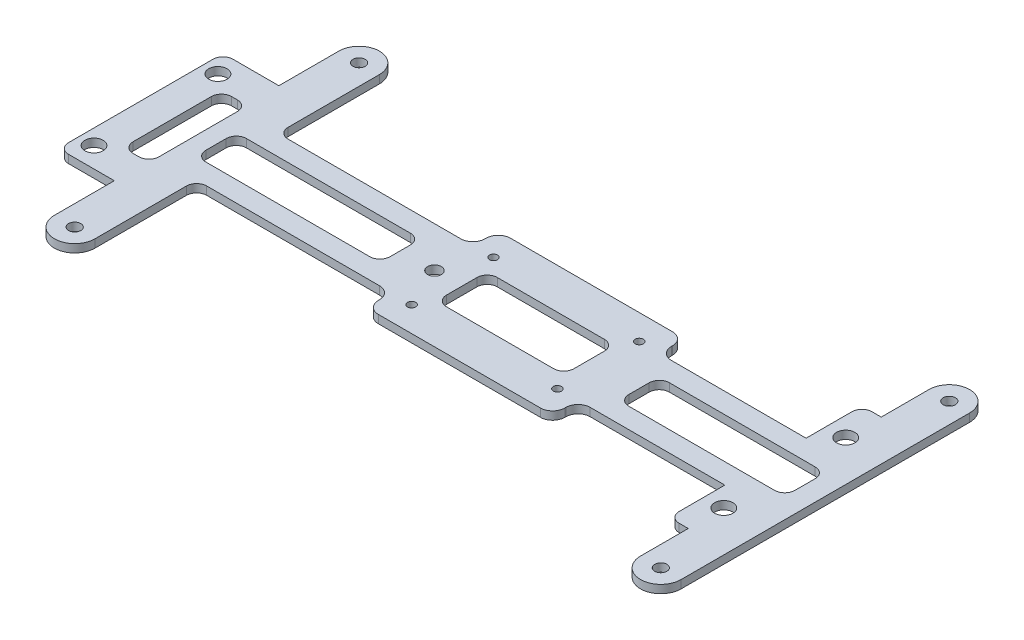
SolidWorks part; units mm, degrees
ref_plane "Alzado" through (0, 0, 0) normal (0, 0, 1) x (1, 0, 0)
ref_plane "Planta" through (0, 0, 0) normal (0, 1, 0) x (1, 0, 0)
ref_plane "Vista lateral" through (0, 0, 0) normal (1, 0, 0) x (0, 0, -1)
sketch "Croquis1" plane through (0, 0, 0) normal (0, 1, 0) x (1, 0, 0)
  line L0 (0, -35.5) -> (0, 35.5)
  line L1 (5, 40.5) -> (27.5, 40.5)
  line L2 (27.5, 40.5) -> (27.5, 70)
  line L3 (47.5, 70) -> (47.5, 25)
  line L4 (52.5, 20) -> (137.5, 20)
  line L5 (143.5, 26) -> (143.5, 26.5)
  line L6 (149.5, 32.5) -> (229.25, 32.5)
  line L7 (235.25, 26.5) -> (235.25, 26)
  line L8 (241.25, 20) -> (307.5, 20)
  line L9 (307.5, 20) -> (307.5, 42.5)
  line L10 (312.5, 47.5) -> (317, 47.5)
  line L11 (317, 47.5) -> (317, 71)
  line L13 (15.5, -24.25) -> (15.5, 24.25)
  line L15 (15.5, 24.25) -> (28.3, 24.25)
  line L16 (28.3, -24.25) -> (28.3, 24.25)
  line L17 (0, 0) -> (337, 0) construction
  line L18 (158, -12.5) -> (220.75, -12.5)
  line L19 (337, -71) -> (337, 71)
  line L21 (37.05, -10) -> (37.05, 10)
  line L22 (37.05, 10) -> (127.75, 10)
  line L23 (127.75, -10) -> (127.75, 10)
  line L24 (37.05, -10) -> (127.75, -10)
  line L25 (15.5, -24.25) -> (28.3, -24.25)
  line L29 (158, -12.5) -> (158, 12.5)
  line L31 (158, 12.5) -> (220.75, 12.5)
  line L32 (220.75, -12.5) -> (220.75, 12.5)
  line L33 (5, -40.5) -> (27.5, -40.5)
  line L34 (27.5, -40.5) -> (27.5, -70)
  line L37 (245.25, -10) -> (245.25, 10)
  line L38 (245.25, 10) -> (327, 10)
  line L39 (327, -10) -> (327, 10)
  line L40 (47.5, -70) -> (47.5, -25)
  line L41 (52.5, -20) -> (137.5, -20)
  line L43 (143.5, -26) -> (143.5, -26.5)
  line L44 (149.5, -32.5) -> (229.25, -32.5)
  line L45 (235.25, -26.5) -> (235.25, -26)
  line L46 (241.25, -20) -> (307.5, -20)
  line L47 (307.5, -20) -> (307.5, -42.5)
  line L48 (312.5, -47.5) -> (317, -47.5)
  line L49 (317, -47.5) -> (317, -71)
  line L50 (245.25, -10) -> (327, -10)
  arc A0 (47.5, 70) -> (27.5, 70) centre (37.5, 70) ccw
  circle A1 centre (37.5, 70) radius 3
  circle A2 centre (144.6, 0) radius 3.4
  arc A3 (317, 71) -> (337, 71) centre (327, 71) cw
  circle A4 centre (153.5, 20.15) radius 2
  circle A5 centre (225.25, 20.15) radius 2
  circle A6 centre (317, 30) radius 4.5
  circle A7 centre (327, 71) radius 3
  circle A8 centre (7.5, 30.5) radius 4.5
  circle A9 centre (327, -71) radius 3
  circle A10 centre (317, -30) radius 4.5
  circle A11 centre (225.25, -20.15) radius 2
  circle A12 centre (153.5, -20.15) radius 2
  circle A13 centre (37.5, -70) radius 3
  circle A14 centre (7.5, -30.5) radius 4.5
  arc A15 (47.5, -70) -> (27.5, -70) centre (37.5, -70) cw
  arc A16 (317, -71) -> (337, -71) centre (327, -71) ccw
  arc A17 (307.5, -42.5) -> (312.5, -47.5) centre (312.5, -42.5) ccw
  arc A18 (307.5, 42.5) -> (312.5, 47.5) centre (312.5, 42.5) cw
  arc A19 (47.5, -25) -> (52.5, -20) centre (52.5, -25) cw
  arc A20 (47.5, 25) -> (52.5, 20) centre (52.5, 25) ccw
  arc A21 (5, -40.5) -> (0, -35.5) centre (5, -35.5) cw
  arc A22 (0, 35.5) -> (5, 40.5) centre (5, 35.5) cw
  arc A23 (229.25, -32.5) -> (235.25, -26.5) centre (229.25, -26.5) ccw
  arc A24 (235.25, -26) -> (241.25, -20) centre (241.25, -26) cw
  arc A25 (143.5, -26.5) -> (149.5, -32.5) centre (149.5, -26.5) ccw
  arc A26 (137.5, -20) -> (143.5, -26) centre (137.5, -26) cw
  arc A27 (235.25, 26) -> (241.25, 20) centre (241.25, 26) ccw
  arc A28 (229.25, 32.5) -> (235.25, 26.5) centre (229.25, 26.5) cw
  arc A29 (143.5, 26.5) -> (149.5, 32.5) centre (149.5, 26.5) cw
  arc A30 (137.5, 20) -> (143.5, 26) centre (137.5, 26) ccw
  point P21 (158, 0)
  point P28 (307.5, -47.5)
  point P31 (189.375, 32.5)
  point P48 (307.5, 47.5)
  point P59 (189.375, 12.5)
  point P79 (47.5, -20)
  point P87 (47.5, 20)
  point P90 (0, -40.5)
  point P93 (0, 40.5)
  point P96 (235.25, -32.5)
  point P99 (235.25, -20)
  point P102 (143.5, -32.5)
  point P105 (143.5, -20)
  point P108 (235.25, 20)
  point P111 (235.25, 32.5)
  point P114 (143.5, 32.5)
  point P117 (143.5, 20)
  dimension "D5" = 6
  dimension "D15" = 3.4
  dimension "D19" = 4
  dimension "D23" = 9
  dimension "D25" = 6
  dimension "D29" = 9
  dimension "D38" = 5
  dimension "D39" = 6
  dimension "D1" = 40.5
  dimension "D2" = 27.5
  dimension "D3" = 20
  dimension "D4" = 70
  dimension "D6" = 337
  dimension "D7" = 15.5
  dimension "D8" = 12.8
  dimension "D9" = 90.7
  dimension "D10" = 8.75
  dimension "D11" = 260
  dimension "D12" = 10
  dimension "D13" = 12.35
  dimension "D14" = 106
  dimension "D16" = 16.25
  dimension "D17" = 62.75
  dimension "D18" = 20
  dimension "D20" = 24.5
  dimension "D21" = 71.75
  dimension "D22" = 20
  dimension "D24" = 25
  dimension "D26" = 16.85
  dimension "D27" = 13.4
  dimension "D28" = 17.5
  dimension "D30" = 142
  dimension "D31" = 7.5
  dimension "D32" = 10
  dimension "D33" = 37.5
  dimension "D34" = 9.5
  dimension "D35" = 10
  dimension "D36" = 20
  dimension "D37" = 10
extrude "Saliente-Extruir1" add sketch "Croquis1" along normal blind 4
fillet "Redondeo1" radius 5 16 edges at (15.5, 2, 24.25) (15.5, 2, -24.25) (28.3, 2, 24.25) (28.3, 2, -24.25) (245.25, 2, 10) (327, 2, 10) (327, 2, -10) (245.25, 2, -10) (158, 2, 12.5) (220.75, 2, 12.5) (220.75, 2, -12.5) (158, 2, -12.5) (127.75, 2, 10) (37.05, 2, 10) (127.75, 2, -10) (37.05, 2, -10)
